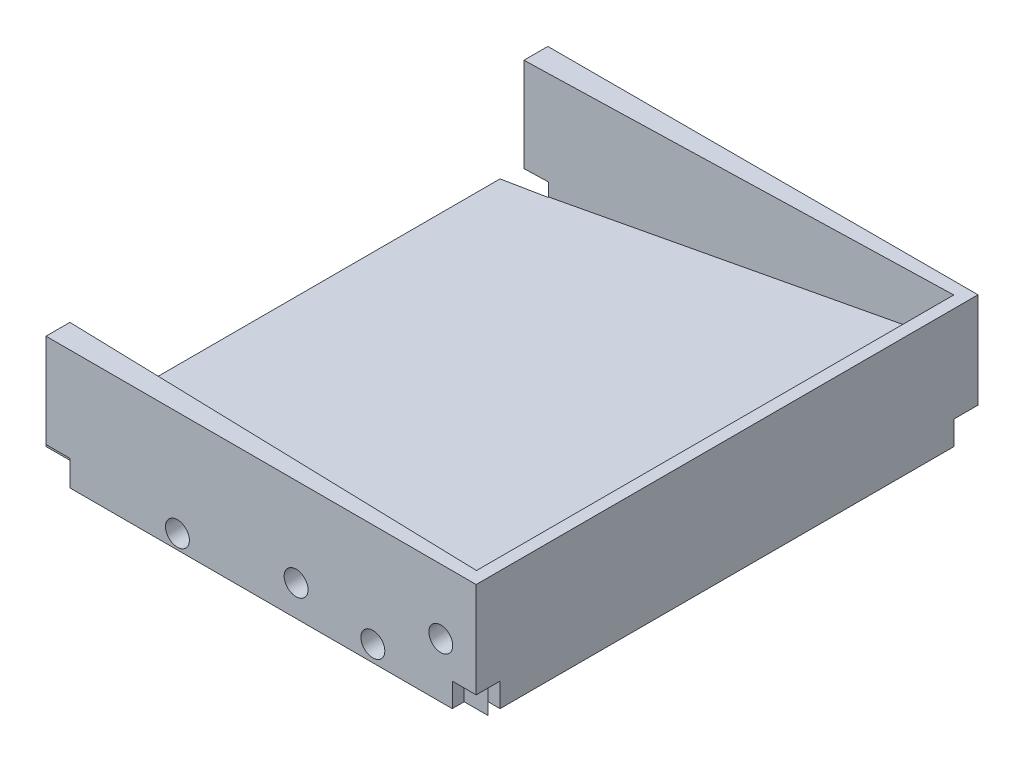
SolidWorks part; units mm, degrees
ref_plane "Plan de face" through (0, 0, 0) normal (0, 0, 1) x (1, 0, 0)
ref_plane "Plan de dessus" through (0, 0, 0) normal (0, 1, 0) x (1, 0, 0)
ref_plane "Plan de droite" through (0, 0, 0) normal (1, 0, 0) x (0, 0, -1)
sketch "Esquisse1" plane through (0, 0, 0) normal (0, 0, 1) x (1, 0, 0)
  line L0 (-105.796, 0) -> (84.204, 0)
  line L1 (84.204, 0) -> (84.204, 33.5021)
  line L2 (84.204, 25.3929) -> (-68.9493, 0) construction
  line L3 (-105.796, 0) -> (-105.796, 2)
  line L4 (-105.796, 2) -> (84.204, 33.5021)
  line L5 (40.9815, 6.7762) -> (8.8615, 12.9011) construction
  line L6 (69.406, 22.9394) -> (40.9815, 6.7762) construction
  circle A0 centre (69.406, 22.9394) radius 3
  circle A1 centre (40.9815, 6.7762) radius 3
  circle A2 centre (-40.796, 6) radius 3
  circle A3 centre (8.8615, 12.9011) radius 3
  dimension "D3" = 6
  dimension "D6" = 6
  dimension "D8" = 6
  dimension "D11" = 6
  dimension "D1" = 190
  dimension "D2" = 2
  dimension "D4" = 15
  dimension "D7" = 8
  dimension "D9" = 6
  dimension "D10" = 65
extrude "Boss.-Extru.1" add sketch "Esquisse1" along normal blind 200
sketch "Esquisse4" plane through (84.204, 0, 0) normal (1, 0, 0) x (0, 0, -1)
  line L1 (-200, 0) -> (-205, 0)
  line L2 (-200, 0) -> (-200, 50)
  line L3 (-200, 50) -> (-205, 50)
  line L4 (-205, 0) -> (-205, 50)
  line L5 (0, 0) -> (5, 0)
  line L6 (0, 0) -> (0, 50)
  line L7 (0, 50) -> (5, 50)
  line L8 (5, 0) -> (5, 50)
  dimension "D1" = 50
  dimension "D2" = 5
  dimension "D3" = 5
  dimension "D4" = 50
extrude "Boss.-Extru.4" add sketch "Esquisse4" against normal blind 180
sketch "Esquisse8" plane through (0, 50, 0) normal (0, 1, 0) x (1, 0, 0)
  line L0 (84.204, 0) -> (-95.796, 0)
  line L1 (-95.796, 0) -> (-95.796, -5)
  line L2 (-95.796, -5) -> (84.204, 0)
  dimension "D1" = 5
extrude "Boss.-Extru.7" add sketch "Esquisse8" against normal up to surface (50 mm away)
ref_plane "Plan2" through (-5.796, 0, 0) normal (1, 0, 0) x (0, 0, -1)
sketch "Esquisse6" plane through (0, 0, -5) normal (0, 0, -1) x (-1, 0, 0)
  line L1 (105.796, 0) -> (85.796, 0)
  line L2 (105.796, 0) -> (105.796, 10.7198)
  line L3 (105.796, 10.7198) -> (85.796, 10.7198)
  line L4 (85.796, 0) -> (85.796, 10.7198)
  line L5 (95.796, 0) -> (95.796, 50) construction
  dimension "D1" = 10
extrude "Enlèv. mat.-Extru.2" cut sketch "Esquisse6" against normal blind 10
ref_plane "Plan3" through (0, 0, 100) normal (0, 0, -1) x (-1, 0, 0)
sketch "Esquisse5" plane through (84.204, 0, 0) normal (1, 0, 0) x (0, 0, -1)
  line L1 (-205, 0) -> (-195, 0)
  line L2 (-205, 0) -> (-205, 10)
  line L3 (-205, 10) -> (-195, 10)
  line L4 (-195, 0) -> (-195, 10)
  line L5 (5, 0) -> (-5, 0)
  line L6 (5, 0) -> (5, 10)
  line L7 (5, 10) -> (-5, 10)
  line L8 (-5, 0) -> (-5, 10)
  dimension "D1" = 10
  dimension "D2" = 10
  dimension "D3" = 10
  dimension "D4" = 10
extrude "Enlèv. mat.-Extru.1" cut sketch "Esquisse5" against normal blind 10
sketch "Esquisse14" plane through (0, 0, -5) normal (0, 0, -1) x (-1, 0, 0)
  circle A0 centre (-69.406, 22.9394) radius 5
  circle A1 centre (-40.9815, 6.7762) radius 5
  circle A2 centre (-8.8615, 12.9011) radius 5
  circle A3 centre (40.796, 6) radius 5
  dimension "D1" = 10
  dimension "D2" = 10
  dimension "D3" = 10
  dimension "D4" = 10
extrude "Enlèv. mat.-Extru.4" cut sketch "Esquisse14" against normal blind 15
mirror "Symétrie3" about plane through (0, 0, 100) normal (0, 0, -1) of "Enlèv. mat.-Extru.4", "Boss.-Extru.7", "Enlèv. mat.-Extru.2"
sketch "Esquisse15" plane through (0, 0, -5) normal (0, 0, -1) x (-1, 0, 0)
  line L0 (-84.204, 33.5021) -> (-79.204, 32.6731)
  line L1 (-84.204, 33.5021) -> (85.796, 5.316) construction
  line L2 (-79.204, 32.6731) -> (-79.204, 50)
  line L3 (95.796, 50) -> (-84.204, 50) construction
  line L4 (-79.204, 50) -> (-84.204, 50)
  line L5 (-84.204, 50) -> (-84.204, 33.5021)
  dimension "D1" = 5
extrude "Boss.-Extru.8" add sketch "Esquisse15" against normal up to surface (204.8611 mm away)
